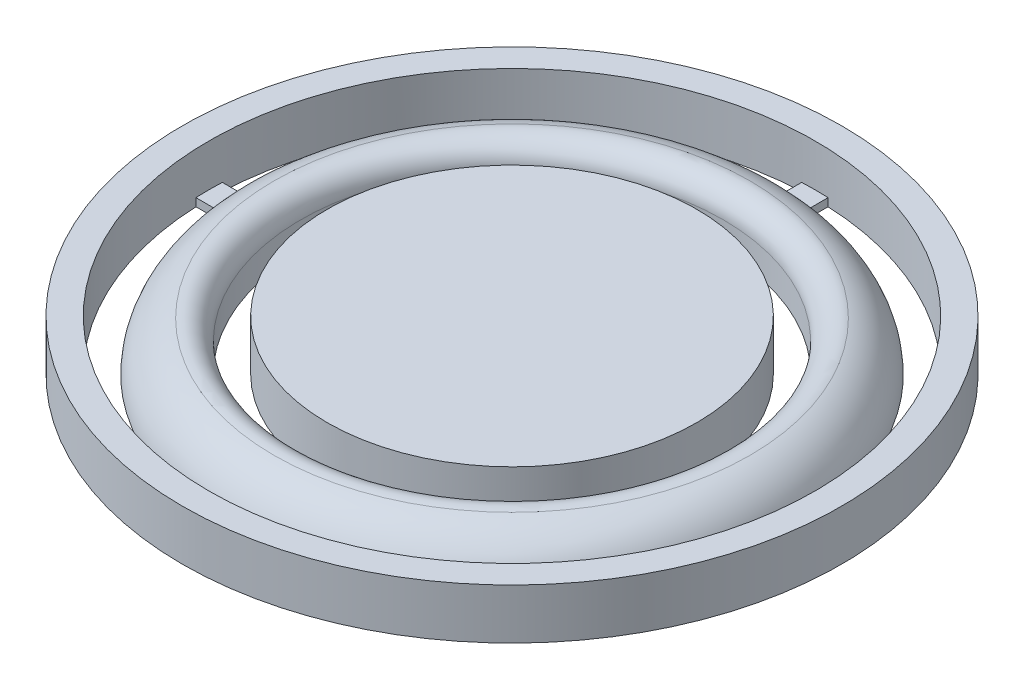
SolidWorks part; units mm, degrees
ref_plane "Front Plane" through (0, 0, 0) normal (0, 0, 1) x (1, 0, 0)
ref_plane "Top Plane" through (0, 0, 0) normal (0, 1, 0) x (1, 0, 0)
ref_plane "Right Plane" through (0, 0, 0) normal (1, 0, 0) x (0, 0, -1)
sketch "Sketch1" plane through (0, 0, 0) normal (0, 1, 0) x (1, 0, 0)
  circle A0 centre (0, 0) radius 80
  circle A1 centre (0, 0) radius 105
  dimension "D1" = 160
  dimension "D2" = 25
extrude "Boss-Extrude1" add sketch "Sketch1" along normal blind 19.05
sketch "Sketch3" plane through (0, 0, 0) normal (0, 0, 1) x (1, 0, 0)
  line L0 (-79.8492, 0) -> (-79.8492, -10.279) construction
  line L1 (-79.8492, -10.279) -> (-110, -10.279) construction
  line L2 (-110, -10.279) -> (-110, 24.05) construction
  line L3 (-110, 24.05) -> (-79.8492, 24.05) construction
  line L4 (-79.8492, 24.05) -> (-79.8492, 19.05) construction
  line L5 (-79.8492, 19.05) -> (-79.8492, 0) construction
  line L6 (-79.8492, 19.05) -> (-84.8492, 19.05) construction
  line L8 (-104.8266, 0) -> (-110, 0) construction
  line L10 (-84.8492, 19.05) -> (-84.8492, 24.05)
  line L11 (-84.8492, 24.05) -> (-110, 24.05)
  line L12 (-110, 24.05) -> (-110, 0)
  line L13 (-110, 0) -> (-104.8266, 0)
  line L14 (0, 0) -> (0, 19.05) construction
  circle A0 centre (-84.8492, -0.95) radius 20 construction
  arc A1 (-84.8492, 19.05) -> (-104.8266, 0) centre (-84.8492, -0.95) ccw
  dimension "D2" = 40
  dimension "D1" = 5
  dimension "D3" = 5
revolve "Cut-Revolve1" cut sketch "Sketch3" angle 360 about L14
sketch "Sketch2" plane through (0, 19.05, 0) normal (0, 1, 0) x (1, 0, 0)
  line L0 (0, 0) -> (0, -105) construction
  line L1 (6.35, -105) -> (-6.35, -105)
  line L2 (-6.35, -105) -> (-6.35, -90) construction
  line L3 (-6.35, -90) -> (6.35, -90)
  line L4 (6.35, -90) -> (6.35, -105) construction
  line L5 (0, -80) -> (0, -90) construction
  line L6 (6.35, -96.4) -> (6.35, -105)
  line L7 (-6.35, -96.4) -> (-6.35, -105)
  circle A1 centre (0, 0) radius 80 construction
  arc A2 (-6.35, -90) -> (-6.35, -96.4) centre (-6.35, -93.2) ccw
  arc A3 (6.35, -96.4) -> (6.35, -90) centre (6.35, -93.2) ccw
  point P8 (0, -105)
  dimension "D3" = 6.4
  dimension "D1" = 10
  dimension "D2" = 12.7
  dimension "D4" = 15
extrude "Cut-Extrude1" [suppressed] cut sketch "Sketch2" against normal through all
fillet "Fillet1" [suppressed] radius 1
pattern_circular "CirPattern1" [suppressed] count 3 over 360
fillet "Fillet4" radius 8 1 edges at (0, 19.05, 80)
sketch "Sketch6" plane through (0, 0, 0) normal (0, 1, 0) x (1, 0, 0)
  line L0 (0, 0) -> (0, 114.8266) construction
  line L1 (0, 0) -> (0, 104.8266) construction
  line L2 (5, 0) -> (5, 114.8266)
  line L3 (-5, 0) -> (-5, 114.8266)
  line L4 (5, 0) -> (-5, 0)
  line L5 (5, 114.8266) -> (-5, 114.8266)
  circle A1 centre (0, 0) radius 104.8266 construction
  dimension "D1" = 10
  dimension "D2" = 5
  dimension "D3" = 5
extrude "Boss-Extrude2" add sketch "Sketch6" along normal blind 3
pattern_circular "CirPattern2" count 4 over 360 about axis through (0, 0, 0) along (0, 1, 0) of "Boss-Extrude2"
sketch "Sketch5" plane through (0, 0, 0) normal (0, 1, 0) x (1, 0, 0)
  circle A0 centre (0, 0) radius 70
  circle A1 centre (0, 0) radius 80 construction
  circle A2 centre (0, 0) radius 114.8266
  circle A3 centre (0, 0) radius 124.8266
  circle A4 centre (0, 0) radius 104.8266 construction
  dimension "D1" = 10
  dimension "D2" = 10
  dimension "D3" = 10
extrude "Boss-Extrude3" add sketch "Sketch5" along normal blind 19.05 contours A0 | A3 A2
